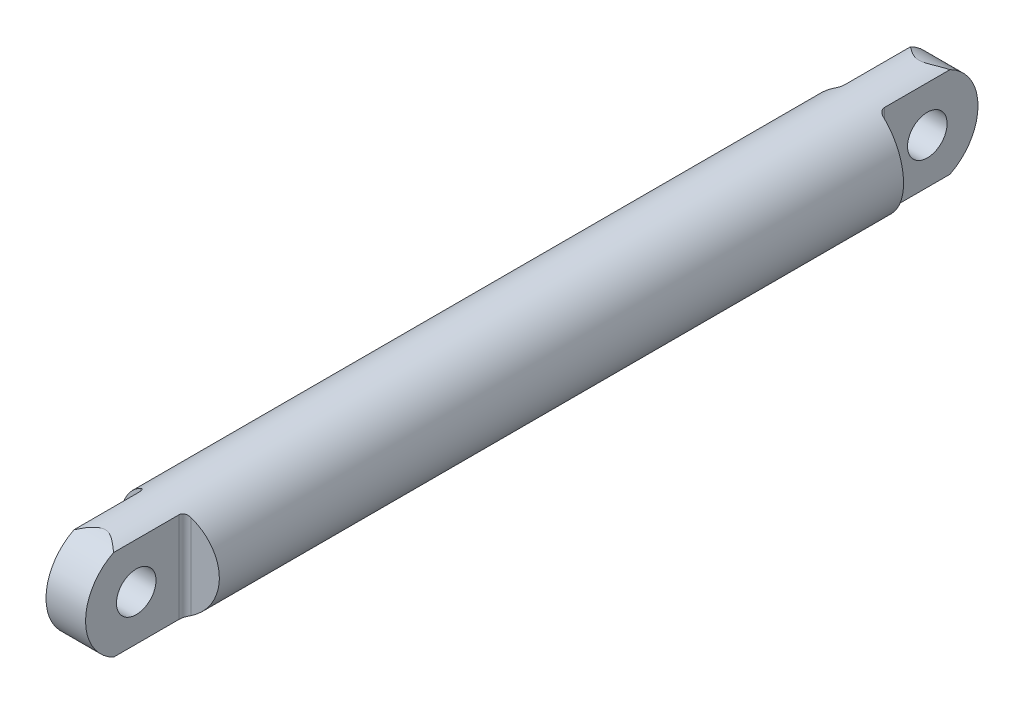
SolidWorks part; units mm, degrees
material "AISI 1045 Steel, cold drawn"
ref_plane "Front Plane" through (0, 0, 0) normal (0, 0, 1) x (1, 0, 0)
ref_plane "Top Plane" through (0, 0, 0) normal (0, 1, 0) x (1, 0, 0)
ref_plane "Right Plane" through (0, 0, 0) normal (1, 0, 0) x (0, 0, -1)
sketch "Sketch1" plane through (0, 0, 0) normal (0, 0, 1) x (1, 0, 0)
  circle A0 centre (0, 0) radius 7.5
  dimension "D1" = 15
extrude "Boss-Extrude1" add sketch "Sketch1" along normal mid plane 135.37
sketch "Sketch6" plane through (0, 0, 0) normal (1, 0, 0) x (0, 0, -1)
  line L8 (67.685, 7.5) -> (67.685, -7.5)
  line L10 (-67.685, -7.5) -> (67.685, -7.5) construction
  line L12 (67.685, 7.5) -> (-67.685, 7.5) construction
  line L13 (67.685, 7.5) -> (61.685, 7.5)
  line L15 (67.685, -7.5) -> (61.685, -7.5)
  arc A1 (61.685, -7.5) -> (61.685, 7.5) centre (59.9975, 0) ccw
  dimension "D1" = 6
extrude "Cut-Extrude2" cut sketch "Sketch6" against normal through all and the other way through all
sketch "Sketch7" plane through (0, 0, 0) normal (0, 1, 0) x (1, 0, 0)
  line L0 (-3, 67.685) -> (-3, 52.685)
  line L4 (-7.5, 67.685) -> (-7.5, -67.685) construction
  line L5 (-7.5, 51.8915) -> (-7.5, 67.685)
  line L6 (-7.5, 67.685) -> (-3, 67.685)
  line L7 (0, 3.0864) -> (0, -9.0403) construction
  line L8 (7.5, 67.685) -> (3, 67.685)
  line L9 (3, 67.685) -> (3, 52.685)
  line L16 (-7.5, 51.8915) -> (-3, 52.685)
  line L21 (3, 52.685) -> (7.5, 51.8915)
  line L22 (7.5, -67.685) -> (7.5, 67.685) construction
  line L23 (7.5, 51.8915) -> (7.5, 67.685)
  dimension "D3" = 100
  dimension "D2" = 15
  dimension "D1" = 3
  dimension "D4" = 100
  dimension "D5" = 3
extrude "Cut-Extrude3" cut sketch "Sketch7" against normal through all both and the other way through all
sketch "Sketch8" plane through (-3, 0, 0) normal (1, 0, 0) x (0, 0, -1)
  circle A0 centre (59.9975, 0) radius 3
  arc A7 (63.4395, -6.8739) -> (63.4395, 6.8739) centre (59.9975, 0) ccw construction
  dimension "D1" = 6
extrude "Cut-Extrude4" cut sketch "Sketch8" against normal through all both and the other way through all contours A0
fillet "Fillet1" radius 1 2 edges at (-3, 0, -52.685) (3, 0, -52.685)
mirror "Mirror2" about plane through (0, 0, 0) normal (0, 0, 1) of "Fillet1", "Cut-Extrude3", "Cut-Extrude2", "Cut-Extrude4"
equation "\"D4@Sketch7\"=\"D3@Sketch7\""
